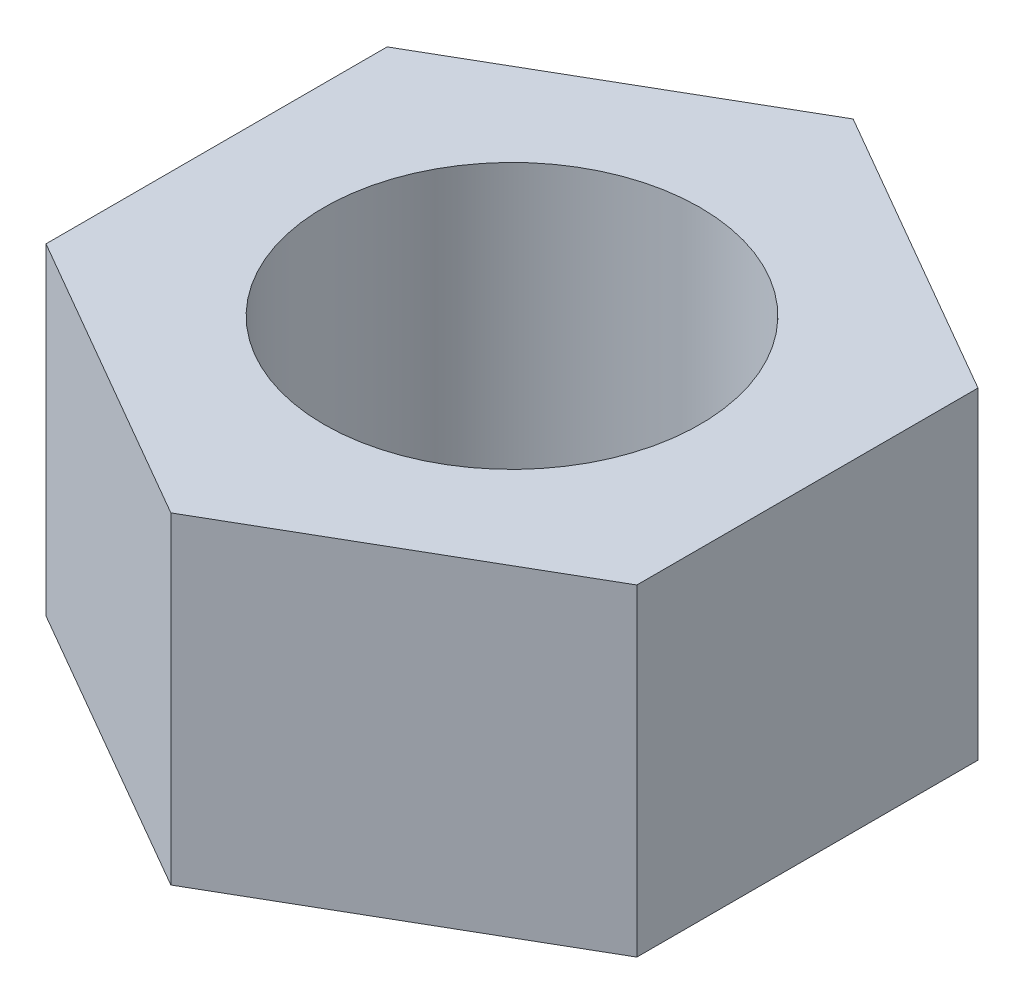
SolidWorks part; units mm, degrees
ref_plane "Front Plane" through (0, 0, 0) normal (0, 0, 1) x (1, 0, 0)
ref_plane "Top Plane" through (0, 0, 0) normal (0, 1, 0) x (1, 0, 0)
ref_plane "Right Plane" through (0, 0, 0) normal (1, 0, 0) x (0, 0, -1)
sketch "Sketch1" plane through (0, 0, 0) normal (0, 1, 0) x (1, 0, 0)
  line L1 (0, 6.3509) -> (-5.5, 3.1754)
  line L2 (-5.5, 3.1754) -> (-5.5, -3.1754)
  line L3 (-5.5, -3.1754) -> (0, -6.3509)
  line L4 (0, -6.3509) -> (5.5, -3.1754)
  line L5 (5.5, -3.1754) -> (5.5, 3.1754)
  line L6 (5.5, 3.1754) -> (0, 6.3509)
  circle A0 centre (0, 0) radius 5.5 construction
  dimension "D1" = 11
extrude "Boss-Extrude1" add sketch "Sketch1" along normal blind 6
sketch "Sketch2" plane through (0, 6, 0) normal (0, 1, 0) x (1, 0, 0)
  circle A0 centre (0, 0) radius 3.5
  dimension "D1" = 7
extrude "Cut-Extrude1" cut sketch "Sketch2" against normal blind 6
